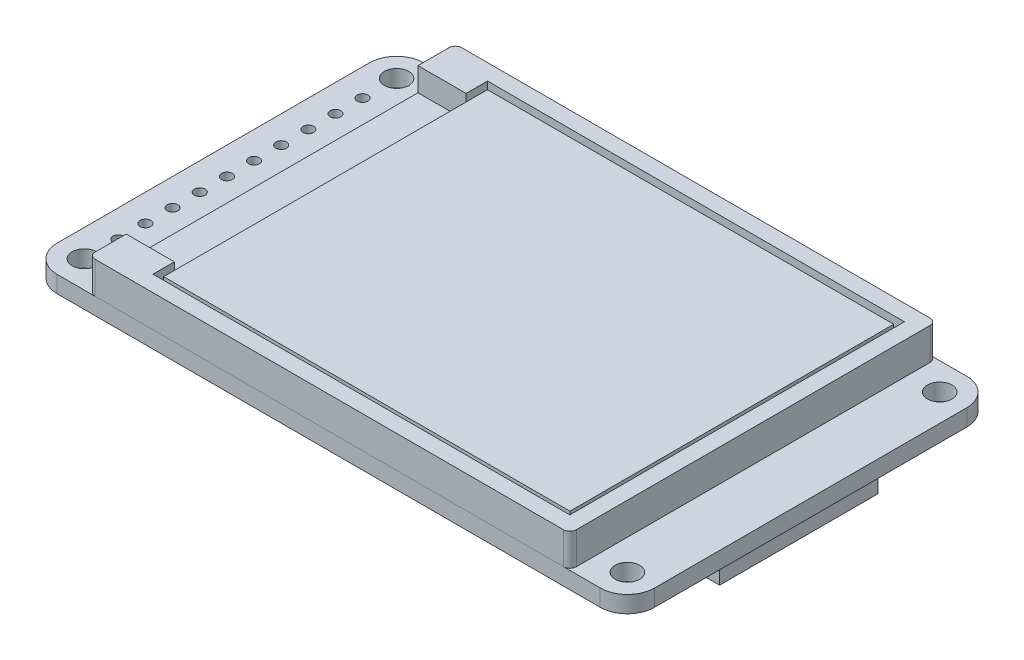
SolidWorks part; units mm, degrees
ref_plane "Front Plane" through (0, 0, 0) normal (0, 0, 1) x (1, 0, 0)
ref_plane "Top Plane" through (0, 0, 0) normal (0, 1, 0) x (1, 0, 0)
ref_plane "Right Plane" through (0, 0, 0) normal (1, 0, 0) x (0, 0, -1)
sketch "Sketch1" plane through (0, 0, 0) normal (0, 1, 0) x (1, 0, 0)
  line L1 (0, 0) -> (55.88, 0)
  line L2 (0, 0) -> (0, 34.29)
  line L3 (0, 34.29) -> (55.88, 34.29)
  line L4 (55.88, 0) -> (55.88, 34.29)
  dimension "D1" = 55.88
  dimension "D2" = 34.29
extrude "Circuit Board" add sketch "Sketch1" along normal blind 1.57
fillet "Fillet1" radius 2.54 4 edges at (0, 0.785, -34.29) (55.88, 0.785, -34.29) (0, 0.785, 0) (55.88, 0.785, 0)
sketch "Sketch2" plane through (0, 1.57, 0) normal (0, 1, 0) x (1, 0, 0)
  circle A0 centre (2.54, 31.75) radius 1.143
  circle A1 centre (53.34, 31.75) radius 1.143
  circle A2 centre (53.34, 2.54) radius 1.143
  circle A3 centre (2.54, 2.54) radius 1.143
  dimension "D1" = 2.286
extrude "Cut-Extrude1" cut sketch "Sketch2" against normal through all
sketch "Sketch3" plane through (0, 1.57, 0) normal (0, 1, 0) x (1, 0, 0)
  line L0 (2.54, 31.75) -> (2.54, 2.54) construction
  line L1 (0, 17.145) -> (55.88, 17.145) construction
  line L2 (0, 31.75) -> (0, 2.54) construction
  line L3 (55.88, 2.54) -> (55.88, 31.75) construction
  circle A0 centre (2.54, 5.715) radius 0.5
  dimension "D1" = 1
  dimension "D2" = 3.175
extrude "Cut-Extrude2" cut sketch "Sketch3" against normal through all
pattern_linear "Connector Holes" count 10 spacing 2.54 along (0, 0, -1) of "Cut-Extrude2"
sketch "Sketch4" plane through (0, 0, 0) normal (0, -1, 0) x (1, 0, 0)
  line L1 (15.9164, -12.5915) -> (22.9996, -12.5915)
  line L2 (15.9164, -12.5915) -> (15.9164, -22.4128)
  line L3 (15.9164, -22.4128) -> (22.9996, -22.4128)
  line L4 (22.9996, -12.5915) -> (22.9996, -22.4128)
  line L5 (40.8565, -9.3773) -> (55.1299, -9.3773)
  line L6 (40.8565, -9.3773) -> (40.8565, -24.1985)
  line L7 (40.8565, -24.1985) -> (55.1299, -24.1985)
  line L8 (55.1299, -9.3773) -> (55.1299, -24.1985)
extrude "IC1 and SD card slot (approximate size and location)" add sketch "Sketch4" along normal blind 2
sketch "Sketch5" plane through (0, 1.57, 0) normal (0, 1, 0) x (1, 0, 0)
  line L0 (53.34, 34.29) -> (2.54, 34.29) construction
  line L1 (5.5, 34.29) -> (50.5, 34.29)
  line L2 (5.5, 34.29) -> (5.5, 0)
  line L3 (5.5, 0) -> (50.5, 0)
  line L4 (50.5, 34.29) -> (50.5, 0)
  line L5 (2.54, 0) -> (53.34, 0) construction
  line L6 (0, 31.75) -> (0, 2.54) construction
  dimension "D1" = 45
  dimension "D2" = 5.5
extrude "Boss-Extrude3" add sketch "Sketch5" along normal blind 3 separate body
sketch "Sketch6" plane through (0, 4.57, 0) normal (0, 1, 0) x (1, 0, 0)
  line L13 (10, 32.79) -> (10, 30.79)
  line L14 (10, 30.79) -> (5.5, 30.79)
  line L15 (5.5, 34.29) -> (5.5, 0) construction
  line L16 (5.5, 30.79) -> (5.5, 3.5)
  line L17 (49, 1.5) -> (49, 32.79)
  line L18 (7, 1.5) -> (49, 1.5)
  line L19 (7, 32.79) -> (7, 1.5)
  line L20 (49, 32.79) -> (7, 32.79)
  line L21 (49, 1.5) -> (49, 32.79)
  line L22 (10, 1.5) -> (49, 1.5)
  line L24 (49, 32.79) -> (10, 32.79)
  line L25 (5.5, 3.5) -> (10, 3.5)
  line L26 (10, 3.5) -> (10, 1.5)
  dimension "D2" = 4.5
  dimension "D3" = 2
  dimension "D1" = 1.5
extrude "Cut-Extrude3" cut sketch "Sketch6" against normal blind 2.2
sketch "Sketch7" plane through (0, 2.37, 0) normal (0, 1, 0) x (1, 0, 0)
  line L0 (10.5, 32.29) -> (10.5, 2)
  line L1 (10, 32.79) -> (49, 32.79) construction
  line L2 (10, 32.79) -> (10, 1.5) construction
  line L3 (10, 1.5) -> (49, 1.5) construction
  line L4 (49, 32.79) -> (49, 1.5) construction
  line L5 (10.5, 2) -> (48.5, 2)
  line L6 (48.5, 32.29) -> (48.5, 2)
  line L7 (10.5, 32.29) -> (48.5, 32.29)
  dimension "D1" = 0.5
extrude "Boss-Extrude4" add sketch "Sketch7" along normal blind 2
fillet "Fillet2" radius 0.6 4 edges at (50.5, 3.07, 0) (50.5, 3.07, -34.29) (5.5, 3.07, -34.29) (5.5, 3.07, 0)
